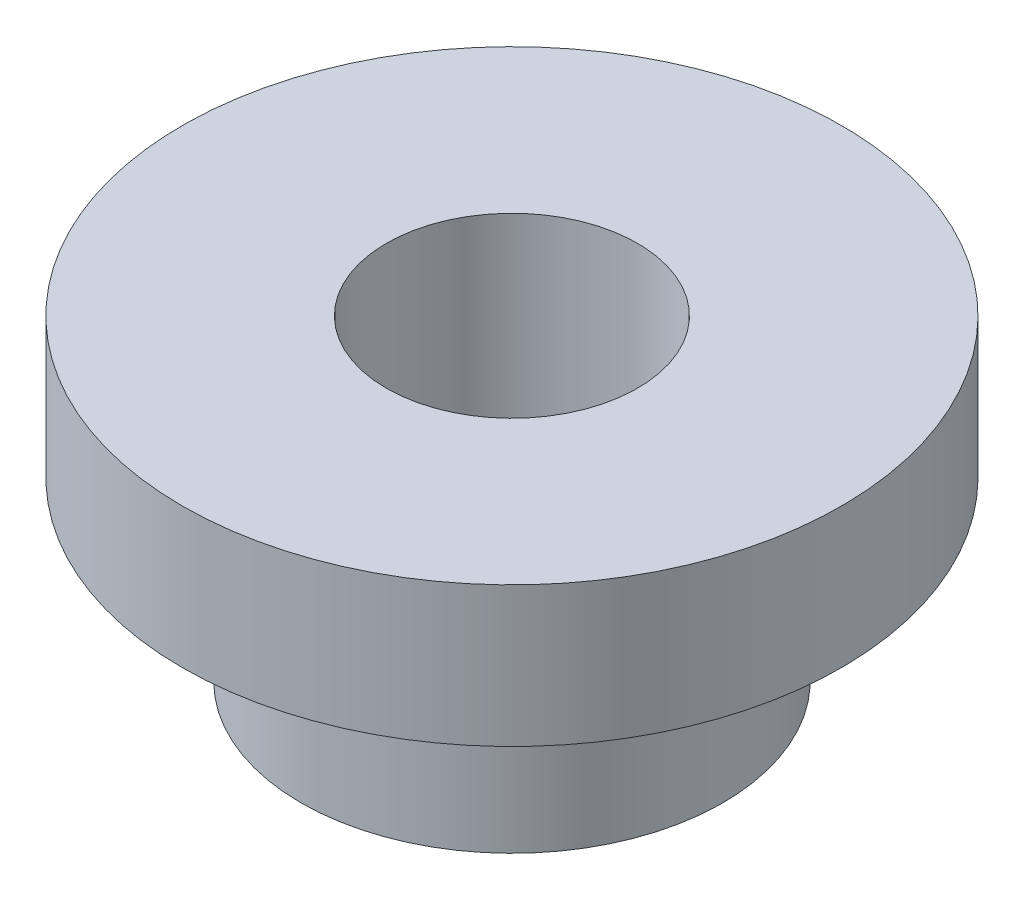
SolidWorks part; units mm, degrees
ref_plane "Front Plane" through (0, 0, 0) normal (0, 0, 1) x (1, 0, 0)
ref_plane "Top Plane" through (0, 0, 0) normal (0, 1, 0) x (1, 0, 0)
ref_plane "Right Plane" through (0, 0, 0) normal (1, 0, 0) x (0, 0, -1)
sketch "Sketch2" plane through (0, 0, 0) normal (0, 0, 1) x (1, 0, 0)
  line L0 (0, 6) -> (0, -6) construction
  line L1 (0.1964, -6) -> (4.7625, -6) construction
  line L2 (4.7625, -6) -> (4.7625, 6)
  line L3 (4.7625, 6) -> (12.5, 6)
  line L4 (12.5, 6) -> (12.5, 0.69)
  line L5 (12.5, 0.69) -> (8, 0.69)
  line L6 (8, 0.69) -> (8, -6)
  line L7 (8, -6) -> (4.7625, -6)
  line L8 (0, 6) -> (4.7625, 6) construction
  point P4 (0, 0)
  dimension "D1" = 12
  dimension "D2" = 5.31
  dimension "D3" = 12.5
  dimension "D4" = 4.7625
  dimension "D5" = 8
revolve "Revolve1" add sketch "Sketch2" angle 360 about L0
